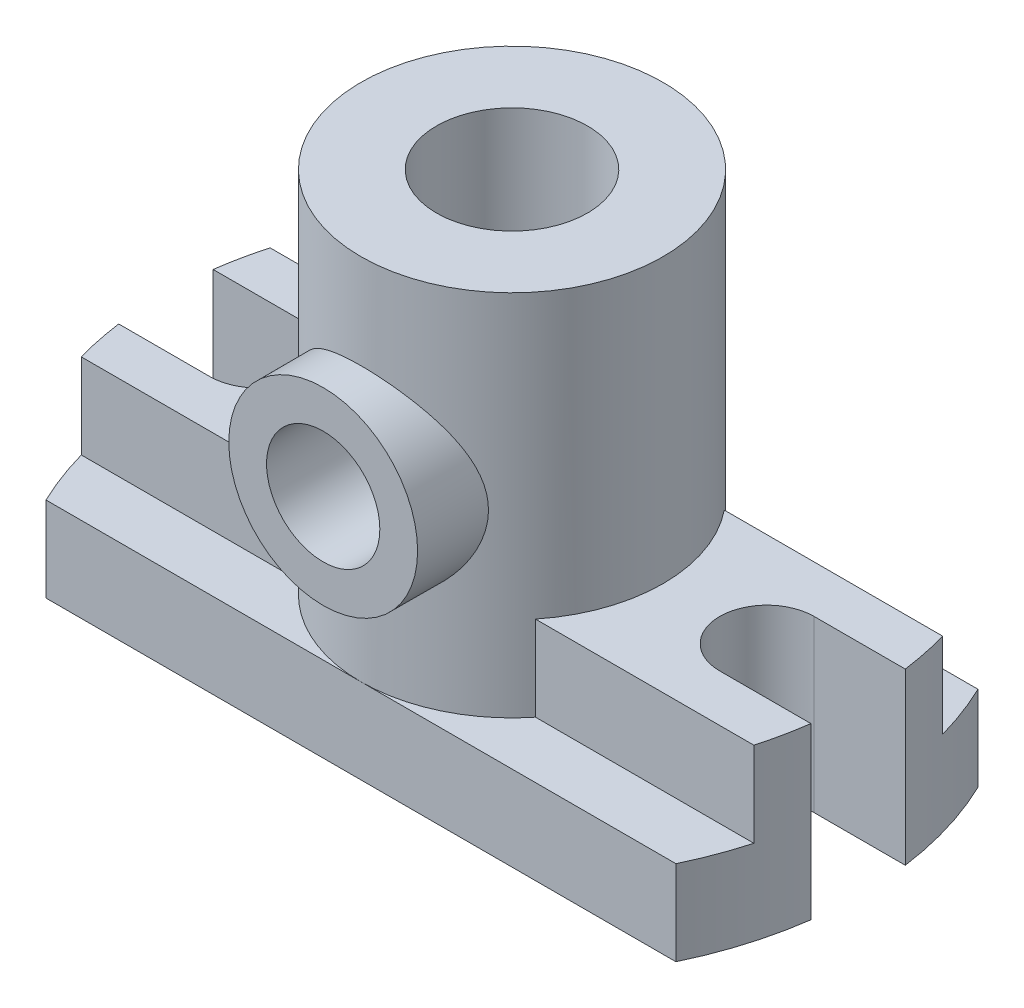
SolidWorks part; units mm, degrees
ref_plane "前视基准面" through (0, 0, 0) normal (0, 0, 1) x (1, 0, 0)
ref_plane "上视基准面" through (0, 0, 0) normal (0, 1, 0) x (1, 0, 0)
ref_plane "右视基准面" through (0, 0, 0) normal (1, 0, 0) x (0, 0, -1)
sketch "草图1" plane through (0, 0, 0) normal (0, 1, 0) x (1, 0, 0)
  line L0 (-61.1692, 0) -> (61.4094, 0) construction
  line L1 (0, 30) -> (0, -30) construction
  line L2 (-35.623, 10) -> (-12.49, 10)
  line L3 (-35.623, -10) -> (-12.49, -10)
  line L4 (-33.3617, 16) -> (0, 16)
  line L5 (-33.3617, -16) -> (0, -16)
  line L6 (12.49, 10) -> (35.623, 10)
  line L7 (12.49, -10) -> (35.623, -10)
  line L8 (-27, 5) -> (-36.6606, 5)
  line L9 (-27, -5) -> (-36.6606, -5)
  line L10 (27, -5) -> (36.6606, -5)
  line L11 (27, 5) -> (36.6606, 5)
  line L12 (0, 16) -> (33.3617, 16)
  line L13 (0, -16) -> (33.3617, -16)
  arc A0 (33.3617, -16) -> (35.623, -10) centre (0, 0) ccw
  arc A1 (-12.49, 10) -> (-12.49, -10) centre (0, 0) ccw
  circle A2 centre (0, 0) radius 8
  arc A3 (-33.3617, 16) -> (-35.623, 10) centre (0, 0) ccw
  arc A4 (-27, -5) -> (-27, 5) centre (-27, 0) ccw
  arc A6 (27, -5) -> (27, 5) centre (27, 0) cw
  arc A7 (-36.6606, -5) -> (-35.623, -10) centre (0, 0) ccw
  arc A8 (36.6606, 5) -> (35.623, 10) centre (0, 0) ccw
  arc A9 (-35.623, 10) -> (-36.6606, 5) centre (0, 0) ccw
  arc A10 (-35.623, -10) -> (-33.3617, -16) centre (0, 0) ccw
  arc A11 (35.623, 10) -> (33.3617, 16) centre (0, 0) ccw
  arc A12 (35.623, -10) -> (36.6606, -5) centre (0, 0) ccw
  arc A13 (12.49, 10) -> (0, 16) centre (0, 0) ccw
  arc A14 (12.49, -10) -> (12.49, 10) centre (0, 0) ccw
  arc A15 (-12.49, -10) -> (0, -16) centre (0, 0) ccw
  arc A16 (0, 16) -> (-12.49, 10) centre (0, 0) ccw
  arc A17 (0, -16) -> (12.49, -10) centre (0, 0) ccw
  point P12 (0, 0)
  point P13 (0, 52.7165)
  point P14 (0, 0)
  point P32 (0, 0)
  point P33 (0, -39.7693)
  point P34 (0, 42.2264)
  point P35 (0, -31.0091)
  point P36 (0, 0)
  point P37 (0, 0)
  dimension "D1" = 74
  dimension "D3" = 32
  dimension "D4" = 16
  dimension "D5" = 5
  dimension "D2" = 20
  dimension "D6" = 54
sketch "草图2" plane through (0, 0, 0) normal (0, 1, 0) x (1, 0, 0)
  line L0 (-61.1692, 0) -> (61.4094, 0) construction
  line L1 (0, 30) -> (0, -30) construction
  line L2 (-35.623, 10) -> (-12.49, 10)
  line L3 (-35.623, -10) -> (-12.49, -10)
  line L4 (-33.3617, 16) -> (0, 16)
  line L5 (-33.3617, -16) -> (0, -16)
  line L6 (12.49, 10) -> (35.623, 10)
  line L7 (12.49, -10) -> (35.623, -10)
  line L8 (-27, 5) -> (-36.6606, 5)
  line L9 (-27, -5) -> (-36.6606, -5)
  line L10 (27, -5) -> (36.6606, -5)
  line L11 (27, 5) -> (36.6606, 5)
  line L12 (0, 16) -> (33.3617, 16)
  line L13 (0, -16) -> (33.3617, -16)
  arc A0 (33.3617, -16) -> (35.623, -10) centre (0, 0) ccw
  arc A1 (-12.49, 10) -> (-12.49, -10) centre (0, 0) ccw
  circle A2 centre (0, 0) radius 8
  arc A3 (-33.3617, 16) -> (-35.623, 10) centre (0, 0) ccw
  arc A4 (-27, -5) -> (-27, 5) centre (-27, 0) ccw
  arc A6 (27, -5) -> (27, 5) centre (27, 0) cw
  arc A7 (-36.6606, -5) -> (-35.623, -10) centre (0, 0) ccw
  arc A8 (36.6606, 5) -> (35.623, 10) centre (0, 0) ccw
  arc A9 (-35.623, 10) -> (-36.6606, 5) centre (0, 0) ccw
  arc A10 (-35.623, -10) -> (-33.3617, -16) centre (0, 0) ccw
  arc A11 (35.623, 10) -> (33.3617, 16) centre (0, 0) ccw
  arc A12 (35.623, -10) -> (36.6606, -5) centre (0, 0) ccw
  arc A13 (12.49, 10) -> (0, 16) centre (0, 0) ccw
  arc A14 (12.49, -10) -> (12.49, 10) centre (0, 0) ccw
  arc A15 (-12.49, -10) -> (0, -16) centre (0, 0) ccw
  arc A16 (0, 16) -> (-12.49, 10) centre (0, 0) ccw
  arc A17 (0, -16) -> (12.49, -10) centre (0, 0) ccw
  point P12 (0, 0)
  point P13 (0, 52.7165)
  point P14 (0, 0)
  point P32 (0, 0)
  point P33 (0, -39.7693)
  point P34 (0, 42.2264)
  point P35 (0, -31.0091)
  point P36 (0, 0)
  point P37 (0, 0)
extrude "凸台-拉伸1" add sketch "草图2" along normal blind 48
sketch "草图3" plane through (0, 0, 0) normal (0, 1, 0) x (1, 0, 0)
  line L0 (-61.1692, 0) -> (61.4094, 0) construction
  line L1 (0, 30) -> (0, -30) construction
  line L2 (-35.623, 10) -> (-12.49, 10)
  line L3 (-35.623, -10) -> (-12.49, -10)
  line L4 (-33.3617, 16) -> (0, 16)
  line L5 (-33.3617, -16) -> (0, -16)
  line L6 (12.49, 10) -> (35.623, 10)
  line L7 (12.49, -10) -> (35.623, -10)
  line L8 (-27, 5) -> (-36.6606, 5)
  line L9 (-27, -5) -> (-36.6606, -5)
  line L10 (27, -5) -> (36.6606, -5)
  line L11 (27, 5) -> (36.6606, 5)
  line L12 (0, 16) -> (33.3617, 16)
  line L13 (0, -16) -> (33.3617, -16)
  arc A0 (33.3617, -16) -> (35.623, -10) centre (0, 0) ccw
  arc A1 (-12.49, 10) -> (-12.49, -10) centre (0, 0) ccw
  circle A2 centre (0, 0) radius 8
  arc A3 (-33.3617, 16) -> (-35.623, 10) centre (0, 0) ccw
  arc A4 (-27, -5) -> (-27, 5) centre (-27, 0) ccw
  arc A6 (27, -5) -> (27, 5) centre (27, 0) cw
  arc A7 (-36.6606, -5) -> (-35.623, -10) centre (0, 0) ccw
  arc A8 (36.6606, 5) -> (35.623, 10) centre (0, 0) ccw
  arc A9 (-35.623, 10) -> (-36.6606, 5) centre (0, 0) ccw
  arc A10 (-35.623, -10) -> (-33.3617, -16) centre (0, 0) ccw
  arc A11 (35.623, 10) -> (33.3617, 16) centre (0, 0) ccw
  arc A12 (35.623, -10) -> (36.6606, -5) centre (0, 0) ccw
  arc A13 (12.49, 10) -> (0, 16) centre (0, 0) ccw
  arc A14 (12.49, -10) -> (12.49, 10) centre (0, 0) ccw
  arc A15 (-12.49, -10) -> (0, -16) centre (0, 0) ccw
  arc A16 (0, 16) -> (-12.49, 10) centre (0, 0) ccw
  arc A17 (0, -16) -> (12.49, -10) centre (0, 0) ccw
  point P12 (0, 0)
  point P13 (0, 52.7165)
  point P14 (0, 0)
  point P32 (0, 0)
  point P33 (0, -39.7693)
  point P34 (0, 42.2264)
  point P35 (0, -31.0091)
  point P36 (0, 0)
  point P37 (0, 0)
extrude "凸台-拉伸2" add sketch "草图3" along normal blind 9
sketch "草图4" plane through (0, 0, 0) normal (0, 1, 0) x (1, 0, 0)
  line L0 (-61.1692, 0) -> (61.4094, 0) construction
  line L1 (0, 30) -> (0, -30) construction
  line L2 (-35.623, 10) -> (-12.49, 10)
  line L3 (-35.623, -10) -> (-12.49, -10)
  line L4 (-33.3617, 16) -> (0, 16)
  line L5 (-33.3617, -16) -> (0, -16)
  line L6 (12.49, 10) -> (35.623, 10)
  line L7 (12.49, -10) -> (35.623, -10)
  line L8 (-27, 5) -> (-36.6606, 5)
  line L9 (-27, -5) -> (-36.6606, -5)
  line L10 (27, -5) -> (36.6606, -5)
  line L11 (27, 5) -> (36.6606, 5)
  line L12 (0, 16) -> (33.3617, 16)
  line L13 (0, -16) -> (33.3617, -16)
  arc A0 (33.3617, -16) -> (35.623, -10) centre (0, 0) ccw
  arc A1 (-12.49, 10) -> (-12.49, -10) centre (0, 0) ccw
  circle A2 centre (0, 0) radius 8
  arc A3 (-33.3617, 16) -> (-35.623, 10) centre (0, 0) ccw
  arc A4 (-27, -5) -> (-27, 5) centre (-27, 0) ccw
  arc A6 (27, -5) -> (27, 5) centre (27, 0) cw
  arc A7 (-36.6606, -5) -> (-35.623, -10) centre (0, 0) ccw
  arc A8 (36.6606, 5) -> (35.623, 10) centre (0, 0) ccw
  arc A9 (-35.623, 10) -> (-36.6606, 5) centre (0, 0) ccw
  arc A10 (-35.623, -10) -> (-33.3617, -16) centre (0, 0) ccw
  arc A11 (35.623, 10) -> (33.3617, 16) centre (0, 0) ccw
  arc A12 (35.623, -10) -> (36.6606, -5) centre (0, 0) ccw
  arc A13 (12.49, 10) -> (0, 16) centre (0, 0) ccw
  arc A14 (12.49, -10) -> (12.49, 10) centre (0, 0) ccw
  arc A15 (-12.49, -10) -> (0, -16) centre (0, 0) ccw
  arc A16 (0, 16) -> (-12.49, 10) centre (0, 0) ccw
  arc A17 (0, -16) -> (12.49, -10) centre (0, 0) ccw
  point P12 (0, 0)
  point P13 (0, 52.7165)
  point P14 (0, 0)
  point P32 (0, 0)
  point P33 (0, -39.7693)
  point P34 (0, 42.2264)
  point P35 (0, -31.0091)
  point P36 (0, 0)
  point P37 (0, 0)
extrude "凸台-拉伸3" add sketch "草图4" along normal blind 18
sketch "草图5" plane through (0, 0, 0) normal (0, 0, 1) x (1, 0, 0)
  circle A0 centre (0, 28) radius 6
  circle A1 centre (0, 28) radius 10
  dimension "D2" = 12
  dimension "D3" = 20
  dimension "D1" = 28
sketch "草图6" plane through (0, 0, 0) normal (0, 0, 1) x (1, 0, 0)
  circle A0 centre (0, 28) radius 6
  circle A1 centre (0, 28) radius 10
extrude "切除-拉伸2" cut sketch "草图5" against normal mid plane 40 contours A0
extrude "凸台-拉伸6" add sketch "草图6" along normal blind 20
extrude "切除-拉伸4" cut sketch "草图1" along normal blind 48 contours A2
